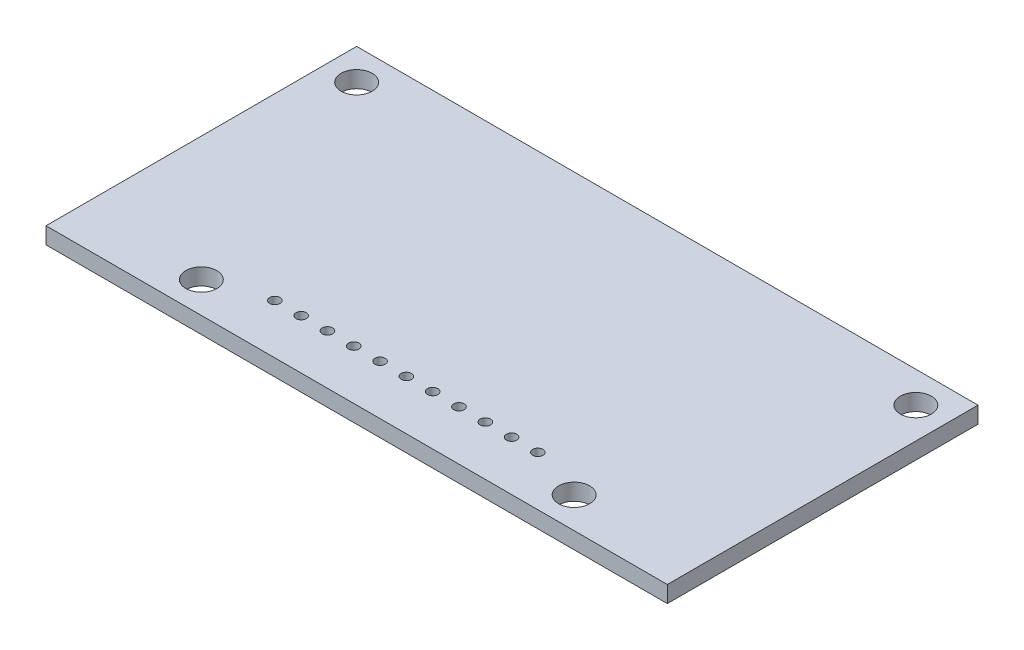
SolidWorks part; units mm, degrees
ref_plane "Front Plane" through (0, 0, 0) normal (0, 0, 1) x (1, 0, 0)
ref_plane "Top Plane" through (0, 0, 0) normal (0, 1, 0) x (1, 0, 0)
ref_plane "Right Plane" through (0, 0, 0) normal (1, 0, 0) x (0, 0, -1)
sketch "Sketch1" plane through (0, 0, 0) normal (0, 1, 0) x (1, 0, 0)
  line L0 (-12.7, -10.2) -> (-10.16, -10.2) construction
  line L1 (30, 15) -> (-30, 15)
  line L2 (30, 15) -> (30, -15)
  line L3 (30, -15) -> (-30, -15)
  line L4 (-30, 15) -> (-30, -15)
  line L5 (30, 15) -> (-30, -15) construction
  line L6 (30, -15) -> (-30, 15) construction
  circle A0 centre (-27, 12) radius 1.5
  circle A1 centre (-18, -12) radius 1.5
  circle A2 centre (18, -12) radius 1.5
  circle A3 centre (27, 12) radius 1.5
  circle A4 centre (-12.7, -10.2) radius 0.5
  circle A5 centre (-10.16, -10.2) radius 0.5
  circle A6 centre (-7.62, -10.2) radius 0.5
  circle A7 centre (-5.08, -10.2) radius 0.5
  circle A8 centre (-2.54, -10.2) radius 0.5
  circle A9 centre (0, -10.2) radius 0.5
  circle A10 centre (2.54, -10.2) radius 0.5
  circle A11 centre (5.08, -10.2) radius 0.5
  circle A12 centre (7.62, -10.2) radius 0.5
  circle A13 centre (10.16, -10.2) radius 0.5
  circle A14 centre (12.7, -10.2) radius 0.5
  point P0 (0, 0)
  dimension "D3" = 3
  dimension "D10" = 1
  dimension "D1" = 60
  dimension "D2" = 30
  dimension "D4" = 3
  dimension "D5" = 3
  dimension "D6" = 3
  dimension "D7" = 12
  dimension "D8" = 3
  dimension "D9" = 12
  dimension "D12" = 2.54
  dimension "D13" = 4.8
  dimension "D11" = 11
extrude "Boss-Extrude1" add sketch "Sketch1" along normal blind 1.6
equation "\"D9@Sketch1\"=\"D7@Sketch1\""
equation "\"D6@Sketch1\"=\"D5@Sketch1\""
